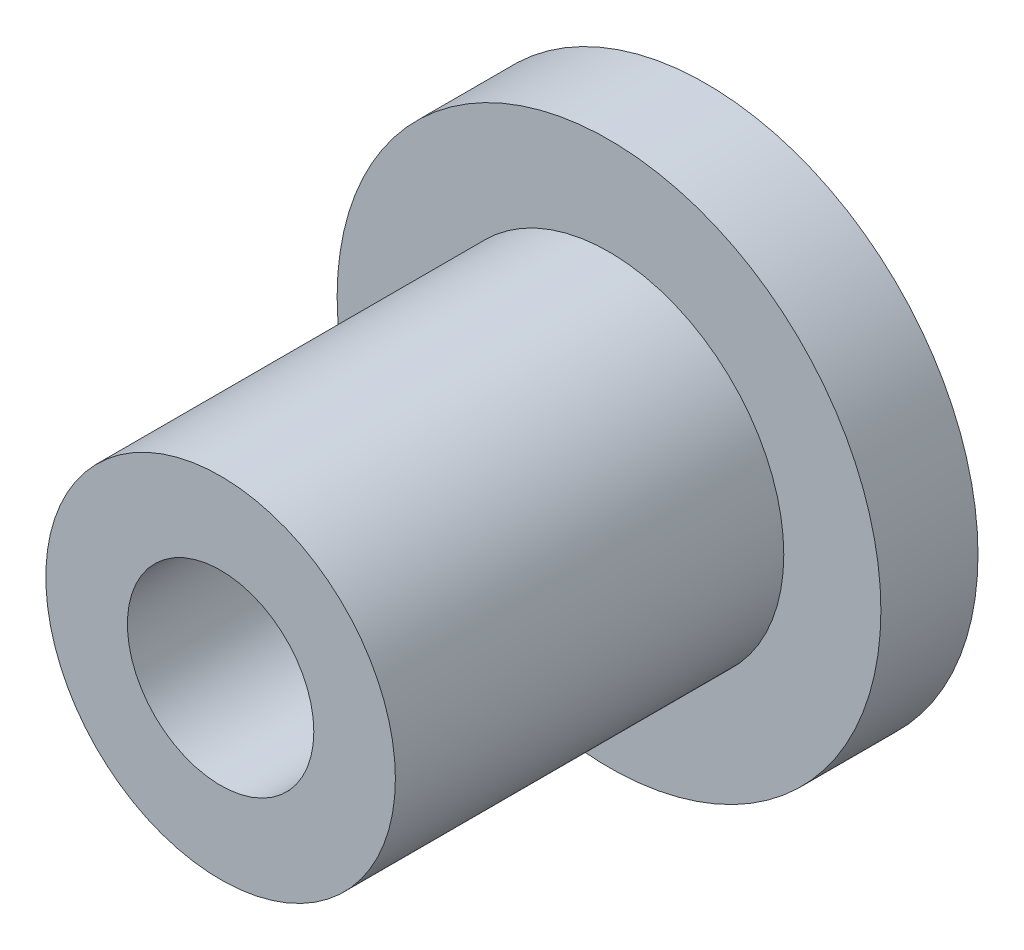
SolidWorks part; units mm, degrees
ref_plane "前视基准面" through (0, 0, 0) normal (0, 0, 1) x (1, 0, 0)
ref_plane "上视基准面" through (0, 0, 0) normal (0, 1, 0) x (1, 0, 0)
ref_plane "右视基准面" through (0, 0, 0) normal (1, 0, 0) x (0, 0, -1)
other "Configuration Table"
sketch "Sketch1" plane through (0, 0, 0) normal (0, 0, 1) x (1, 0, 0)
  circle A0 centre (0, 0) radius 7
  dimension "D1" = 14
extrude "Boss-Extrude1" add sketch "Sketch1" along normal blind 2.5
sketch "Sketch2" plane through (0, 0, 2.5) normal (0, 0, 1) x (1, 0, 0)
  circle A0 centre (0, 0) radius 4.5
  dimension "D1" = 9
extrude "Boss-Extrude2" add sketch "Sketch2" along normal blind 10
sketch "Sketch3" plane through (0, 0, 12.5) normal (0, 0, 1) x (1, 0, 0)
  circle A5 centre (0, 0) radius 2.4
  dimension "D1" = 4.8
extrude "Cut-Extrude1" cut sketch "Sketch3" against normal blind 5
